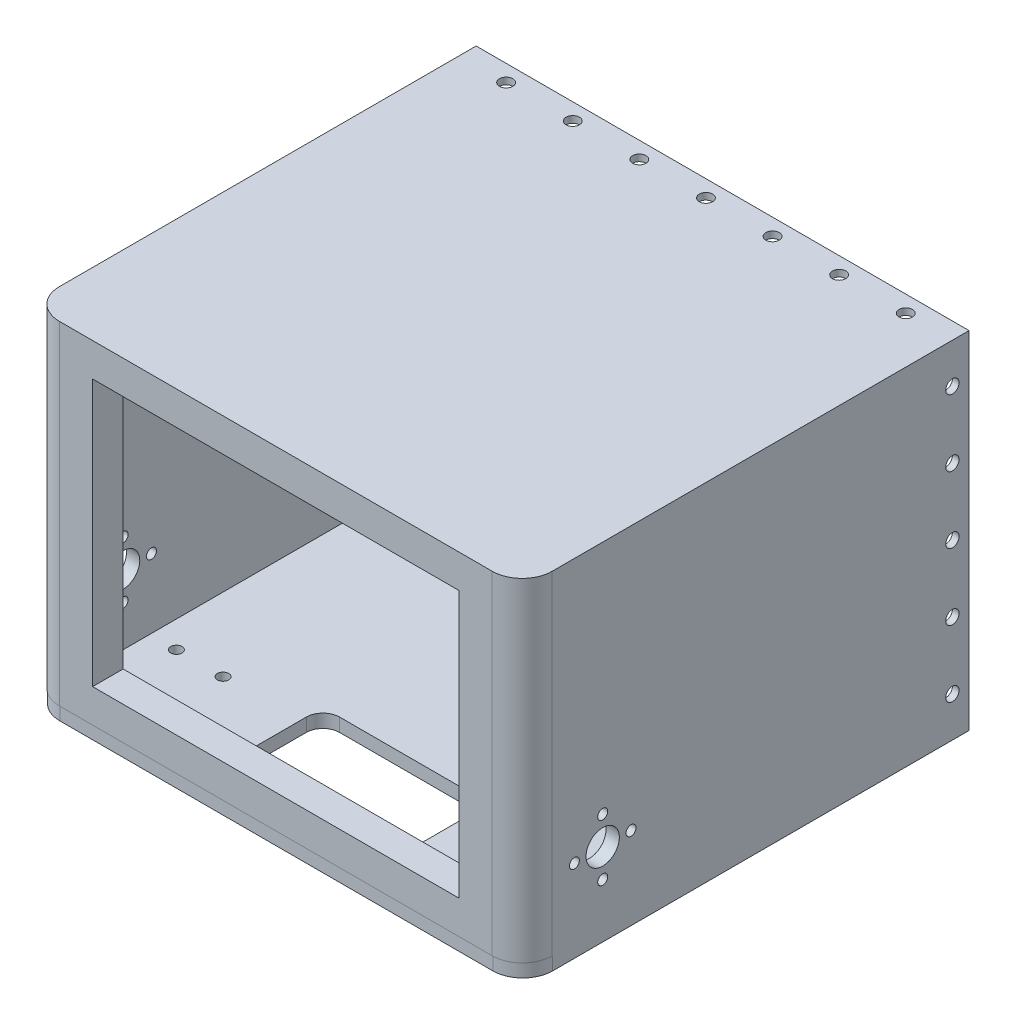
SolidWorks part; units mm, degrees
ref_plane "前视基准面" through (0, 0, 0) normal (0, 0, 1) x (1, 0, 0)
ref_plane "上视基准面" through (0, 0, 0) normal (0, 1, 0) x (1, 0, 0)
ref_plane "右视基准面" through (0, 0, 0) normal (1, 0, 0) x (0, 0, -1)
other "Configuration Table"
sketch "草图1" plane through (0, 0, 0) normal (0, 1, 0) x (1, 0, 0)
  line L0 (0, 120) -> (0, -49880) construction
  line L5 (-1000, 0) -> (49000, 0) construction
  line L6 (-25, -107.9892) -> (-25, -90)
  line L10 (-70, 115) -> (-70, 80)
  line L11 (20, -85) -> (-20, -85)
  line L12 (-70, 120) -> (-70, 113)
  line L13 (-70, 113) -> (-70, 87)
  line L14 (-70, 87) -> (-70, 80)
  line L15 (-70, 113) -> (-40, 113)
  line L16 (-40, 113) -> (-40, 87)
  line L17 (-40, 87) -> (-70, 87)
  line L18 (-70, 113) -> (-70, 108)
  line L19 (-70, 87) -> (-70, 92)
  line L20 (-40, 87) -> (-48, 87)
  line L21 (-48, 87) -> (-48, 92)
  line L22 (-48, 92) -> (-40, 92)
  line L23 (-70, 92) -> (-62, 92)
  line L24 (-62, 92) -> (-62, 87)
  line L25 (-70, 97.5) -> (-40, 97.5) construction
  line L26 (25, -107.9892) -> (25, -90)
  line L27 (25, -100) -> (25, -112.9892)
  line L28 (-70, 80) -> (0, 80)
  line L29 (-65, 120) -> (65, 120)
  line L30 (70, 115) -> (70, 80)
  line L31 (-65, -120) -> (65, -120)
  line L32 (70, -115) -> (70, -80)
  line L33 (-70, -115) -> (-70, -80)
  line L34 (20, 112.9892) -> (-20, 112.9892)
  line L36 (25, -85) -> (5, -85)
  line L38 (-25, 100) -> (-25, 90)
  line L39 (-20, 85) -> (-5, 85)
  line L43 (25, 100) -> (25, 90)
  line L44 (20, 85) -> (5, 85)
  line L46 (25, 100) -> (25, 107.9892)
  line L57 (25, -100) -> (25, -85)
  line L59 (0, 120) -> (0, 110)
  line L60 (-70, 80) -> (-70, -80)
  line L61 (70, -80) -> (70, 80)
  line L62 (25, 112.9892) -> (25, 85)
  line L63 (25, 85) -> (-25, 85)
  line L64 (-25, 107.9892) -> (-25, 85)
  line L65 (-25, -85) -> (-5, -85)
  line L66 (-25, -100) -> (-25, -85)
  line L67 (20, -112.9892) -> (-20, -112.9892)
  line L68 (-1001.7967, 0) -> (48998.2033, 0)
  line L69 (-74, 115) -> (-74, 80)
  line L70 (-65, 124) -> (65, 124)
  line L71 (74, 115) -> (74, 80)
  line L72 (74, -80) -> (74, 80)
  line L73 (74, -115) -> (74, -80)
  line L74 (-65, -124) -> (65, -124)
  line L75 (-74, -115) -> (-74, -80)
  line L76 (-74, 80) -> (-74, -80)
  circle A0 centre (-62, 92) radius 1.7
  circle A1 centre (-48, 92) radius 1.7
  circle A4 centre (48, 108) radius 1.7
  circle A5 centre (48, 92) radius 1.7
  circle A6 centre (62, 92) radius 1.7
  circle A7 centre (62, 108) radius 1.7
  circle A8 centre (62, -108) radius 1.7
  circle A9 centre (62, -92) radius 1.7
  circle A10 centre (48, -92) radius 1.7
  circle A11 centre (48, -108) radius 1.7
  circle A12 centre (-48, -92) radius 1.7
  circle A13 centre (-62, -92) radius 1.7
  circle A14 centre (-48, -108) radius 1.7
  circle A15 centre (-62, -108) radius 1.7
  arc A16 (20, 112.9892) -> (25, 107.9892) centre (20, 107.9892) cw
  arc A17 (25, 90) -> (20, 85) centre (20, 90) cw
  arc A18 (-20, 85) -> (-25, 90) centre (-20, 90) cw
  arc A19 (-25, 107.9892) -> (-20, 112.9892) centre (-20, 107.9892) cw
  arc A20 (20, -85) -> (25, -90) centre (20, -90) cw
  arc A21 (-20, -85) -> (-25, -90) centre (-20, -90) ccw
  arc A22 (-25, -107.9892) -> (-20, -112.9892) centre (-20, -107.9892) ccw
  arc A23 (20, -112.9892) -> (25, -107.9892) centre (20, -107.9892) ccw
  arc A24 (65, -120) -> (70, -115) centre (65, -115) ccw
  arc A25 (-70, -115) -> (-65, -120) centre (-65, -115) ccw
  arc A26 (65, 120) -> (70, 115) centre (65, 115) cw
  arc A27 (-70, 115) -> (-65, 120) centre (-65, 115) cw
  circle A28 centre (-62, 108) radius 1.7
  circle A29 centre (-48, 108) radius 1.7
  arc A30 (-74, 115) -> (-65, 124) centre (-65, 115) cw
  arc A31 (65, 124) -> (74, 115) centre (65, 115) cw
  arc A32 (65, -124) -> (74, -115) centre (65, -115) ccw
  arc A33 (-74, -115) -> (-65, -124) centre (-65, -115) ccw
  point P0 (0, 0)
  point P86 (-25, 112.9892)
  point P95 (-25, -112.9892)
  dimension "D12" = 3.4
  dimension "D13" = 3.4
  dimension "D3" = 5
  dimension "D4" = 40
  dimension "D5" = 7
  dimension "D6" = 7
  dimension "D7" = 30
  dimension "D8" = 5
  dimension "D9" = 5
  dimension "D10" = 8
  dimension "D11" = 8
  dimension "D14" = 4
  dimension "D15" = 15
  dimension "D16" = 8
  dimension "D17" = 20
  dimension "D22" = 10
extrude "凸台-拉伸6" add sketch "草图1" along normal blind 4
sketch "草图9" plane through (0, 4, 0) normal (0, 1, 0) x (1, 0, 0)
  line L1 (-74, 0) -> (74, 0)
  line L2 (-74, 0) -> (-74, -115.1666)
  line L3 (-65, -124.1666) -> (65, -124.1666)
  line L4 (74, 0) -> (74, -115.1666)
  arc A1 (65, -124.1666) -> (74, -115.1666) centre (65, -115.1666) ccw
  arc A2 (-65, -124.1666) -> (-74, -115.1666) centre (-65, -115.1666) cw
  dimension "D1" = 9
extrude "凸台-拉伸7" add sketch "草图9" along normal blind 100
sketch "草图10" plane through (0, 0, 0) normal (0, 0, -1) x (-1, 0, 0)
  line L0 (-70, 100) -> (-70, 4)
  line L1 (-74, 104) -> (74, 104)
  line L3 (-74, 0) -> (74, 0)
  line L4 (74, 104) -> (74, 0)
  line L5 (-70, 4) -> (70, 4)
  line L6 (70, 100) -> (70, 4)
  line L7 (-70, 100) -> (70, 100)
  line L8 (-74, 104) -> (-74, 0) construction
  dimension "D1" = 4
extrude "切除-拉伸20" cut sketch "草图10" against normal blind 115 contours L7 L0 L5 L6
sketch "草图13" plane through (0, 4, 0) normal (0, 1, 0) x (1, 0, 0)
  line L0 (-62, -92) -> (-62, -108) construction
  line L1 (-62, -100) -> (-74, -100)
  line L2 (-74, -115) -> (-74, -80) construction
sketch "草图16" plane through (-74, 0, 0) normal (-1, 0, 0) x (0, 0, 1)
  line L0 (0, 4) -> (100, 4)
  line L1 (0, 4) -> (115.1666, 4) construction
  line L2 (100, 4) -> (100, 24.75)
  line L3 (100, 24.75) -> (108.5, 24.75) construction
  circle A0 centre (100, 24.75) radius 4
  circle A1 centre (108.5, 24.75) radius 1.5
  circle A2 centre (100, 16.25) radius 1.5
  circle A3 centre (91.5, 24.75) radius 1.5
  circle A4 centre (100, 33.25) radius 1.5
  dimension "D3" = 8
  dimension "D5" = 3
  dimension "D1" = 100
  dimension "D2" = 20.75
  dimension "D4" = 8.5
  dimension "D6" = 4
extrude "切除-拉伸22" cut sketch "草图16" along normal through all both and the other way through all
sketch "草图21" plane through (0, 0, 124.1666) normal (0, 0, 1) x (1, 0, 0)
  line L0 (-55, 94) -> (-55, 14)
  line L1 (-65, 104) -> (65, 104)
  line L3 (-65, 4) -> (65, 4)
  line L4 (65, 104) -> (65, 4)
  line L5 (-55, 14) -> (55, 14)
  line L6 (55, 94) -> (55, 14)
  line L7 (-55, 94) -> (55, 94)
  line L8 (-65, 104) -> (-65, 4) construction
  dimension "D1" = 10
extrude "切除-拉伸28" cut sketch "草图21" against normal blind 50 contours L7 L0 L5 L6
sketch "草图22" plane through (0, 0, 0) normal (0, 0, -1) x (-1, 0, 0)
  line L0 (-72, 102) -> (-72, 2)
  line L1 (-74, 104) -> (74, 104)
  line L2 (-74, 104) -> (-74, 0)
  line L3 (-74, 0) -> (74, 0)
  line L4 (74, 104) -> (74, 0)
  line L5 (-72, 2) -> (72, 2)
  line L6 (72, 102) -> (72, 2)
  line L7 (-72, 102) -> (72, 102)
  dimension "D1" = 2
sketch "草图23" plane through (-74, 0, 0) normal (-1, 0, 0) x (0, 0, 1)
  circle A0 centre (100, 24.75) radius 5
  dimension "D1" = 10
extrude "切除-拉伸29" cut sketch "草图23" against normal through all
extrude "凸台-拉伸8" add sketch "草图22" along normal blind 10
sketch "草图27" plane through (0, 102, 0) normal (0, -1, 0) x (1, 0, 0)
  line L0 (0, 0) -> (0, -5)
  line L1 (0, -1005) -> (0, 48995) construction
  circle A0 centre (0, -5) radius 2
  circle A1 centre (20, -5) radius 2
  circle A2 centre (40, -5) radius 2
  circle A3 centre (60, -5) radius 2
  circle A4 centre (-60, -5) radius 2
  circle A5 centre (-40, -5) radius 2
  circle A6 centre (-20, -5) radius 2
  dimension "D2" = 4
  dimension "D1" = 5
  dimension "D3" = 4
extrude "切除-拉伸30" cut sketch "草图27" along normal through all both and the other way through all contours A4 | A5 | A6 | A2 | A0 | A1 | A3
sketch "草图30" plane through (-72, 0, 0) normal (1, 0, 0) x (0, 0, -1)
  line L0 (-990, 52) -> (49010, 52) construction
  line L1 (10, 104) -> (10, 0) construction
  line L2 (10, 52) -> (5, 52)
  circle A0 centre (5, 52) radius 2
  circle A1 centre (5, 72) radius 2
  circle A2 centre (5, 92) radius 2
  circle A3 centre (5, 12) radius 2
  circle A4 centre (5, 32) radius 2
  point P5 (10, 52)
  dimension "D2" = 4
  dimension "D1" = 5
  dimension "D3" = 3
extrude "切除-拉伸31" cut sketch "草图30" against normal through all both and the other way through all contours A2 | A1 | A0 | A4 | A3
